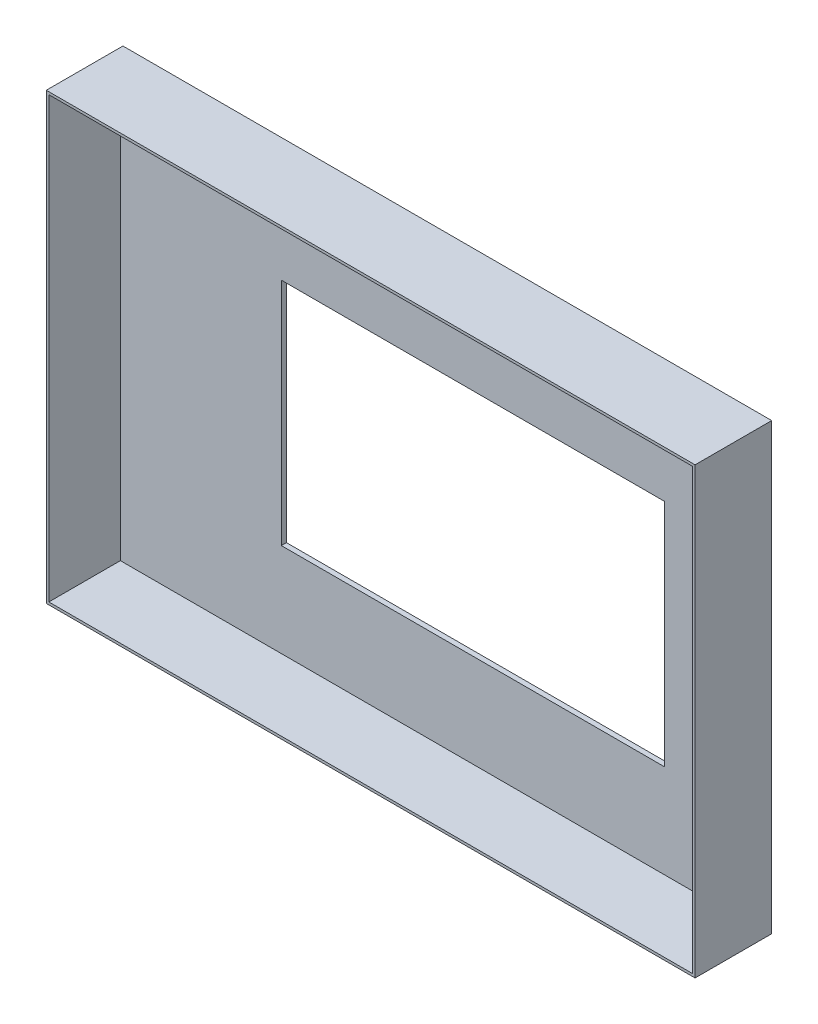
SolidWorks part; units mm, degrees
ref_plane "Front Plane" through (0, 0, 0) normal (0, 0, 1) x (1, 0, 0)
ref_plane "Top Plane" through (0, 0, 0) normal (0, 1, 0) x (1, 0, 0)
ref_plane "Right Plane" through (0, 0, 0) normal (1, 0, 0) x (0, 0, -1)
sketch "Sketch1" plane through (0, 0, 0) normal (0, 0, 1) x (1, 0, 0)
  line L1 (-61.595, 27.305) -> (65.405, 27.305)
  line L2 (-61.595, 27.305) -> (-61.595, -59.695)
  line L3 (-61.595, -59.695) -> (65.405, -59.695)
  line L4 (65.405, 27.305) -> (65.405, -59.695)
  dimension "D1" = 127
  dimension "D2" = 87
extrude "Boss-Extrude1" add sketch "Sketch1" along normal blind 15
sketch "Sketch2" plane through (0, 0, 15) normal (0, 0, 1) x (1, 0, 0)
  line L0 (-61.595, 27.305) -> (-61.595, -59.695) construction
  line L1 (-61.095, 26.805) -> (64.905, 26.805)
  line L2 (-61.095, 26.805) -> (-61.095, -59.195)
  line L3 (-61.095, -59.195) -> (64.905, -59.195)
  line L4 (64.905, 26.805) -> (64.905, -59.195)
  line L5 (65.405, 27.305) -> (-61.595, 27.305) construction
  dimension "D1" = 126
  dimension "D2" = 86
  dimension "D3" = 0.5
  dimension "D4" = 0.5
extrude "Cut-Extrude1" cut sketch "Sketch2" against normal blind 14
sketch "Sketch3" plane through (0, 0, 0) normal (0, 0, -1) x (-1, 0, 0)
  line L0 (-65.405, -59.695) -> (-65.405, 27.305) construction
  line L1 (-45.405, 4.1165) -> (29.595, 4.1165)
  line L2 (-45.405, 4.1165) -> (-45.405, -40.8835)
  line L3 (-45.405, -40.8835) -> (29.595, -40.8835)
  line L4 (29.595, 4.1165) -> (29.595, -40.8835)
  dimension "D1" = 45
  dimension "D2" = 75
  dimension "D3" = 20
extrude "Cut-Extrude2" cut sketch "Sketch3" against normal blind 1
sketch "Sketch9" plane through (0, 0, 0) normal (0, 0, -1) x (-1, 0, 0)
  text T0 "<b><i>SKITWALL </i></b>                    " font "Century Gothic" height 3.175
  text T1 "<b><i>Skills In TVET Without Walls    </i></b>        " font "Century Gothic" height 3.175
